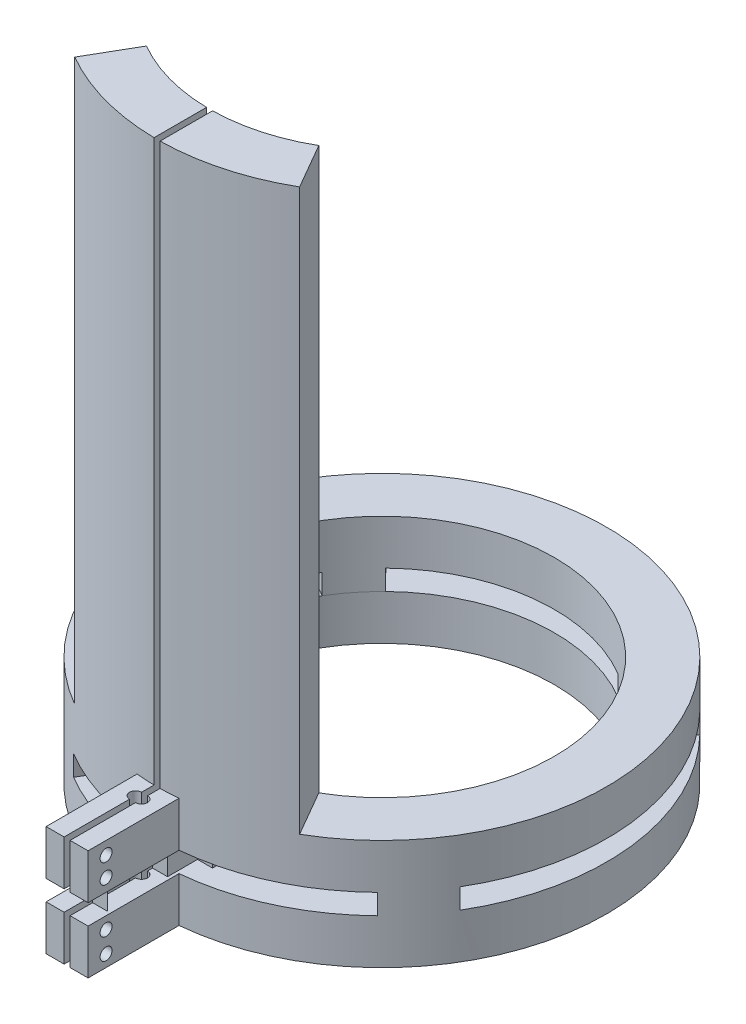
SolidWorks part; units mm, degrees
ref_plane "Front Plane" through (0, 0, 0) normal (0, 0, 1) x (1, 0, 0)
ref_plane "Top Plane" through (0, 0, 0) normal (0, 1, 0) x (1, 0, 0)
ref_plane "Right Plane" through (0, 0, 0) normal (1, 0, 0) x (0, 0, -1)
sketch "Sketch1" plane through (0, 0, 0) normal (0, 1, 0) x (1, 0, 0)
  circle A0 centre (0, 0) radius 57.5
  circle A1 centre (0, 0) radius 75
  dimension "D1" = 115
  dimension "D2" = 150
extrude "Boss-Extrude1" add sketch "Sketch1" along normal blind 15
ref_plane "Plane1" through (0, 0, 75) normal (0, 0, 1) x (1, 0, 0)
sketch "Sketch2" plane through (0, 0, 75) normal (0, 0, 1) x (1, 0, 0)
  line L0 (57.5, 15) -> (-57.5, 15) construction
  line L1 (-7, 15) -> (7, 15)
  line L2 (-7, 15) -> (-7, 0)
  line L3 (-7, 0) -> (7, 0)
  line L4 (7, 15) -> (7, 0)
  line L5 (-75, 0) -> (75, 0) construction
  line L6 (-75, 15) -> (-75, 0) construction
  dimension "D1" = 14
  dimension "D2" = 68
extrude "Boss-Extrude2" add sketch "Sketch2" along normal blind 30 and the other way blind 5
sketch "Sketch5" plane through (0, 0, 0) normal (0, -1, 0) x (1, 0, 0)
  line L0 (-1, 105) -> (-1, 57.4913)
  line L1 (-7, 105) -> (7, 105) construction
  line L2 (1, 105) -> (1, 57.4913)
  line L3 (-1, 105) -> (1, 105)
  line L4 (-1, 57.4913) -> (1, 57.4913)
  line L5 (-7, 74.6726) -> (-7, 105) construction
  line L6 (7, 74.6726) -> (7, 105) construction
  circle A0 centre (0, 0) radius 57.5 construction
  dimension "D1" = 6
  dimension "D2" = 6
extrude "Cut-Extrude2" cut sketch "Sketch5" against normal blind 64
sketch "Sketch6" plane through (7, 0, 0) normal (1, 0, 0) x (0, 0, -1)
  line L0 (-105, 0) -> (-105, 15) construction
  line L1 (-74.6726, 0) -> (-105, 0) construction
  line L2 (-74.6726, 15) -> (-105, 15) construction
  circle A0 centre (-99, 4.25) radius 2
  circle A1 centre (-99, 10.75) radius 2
  point P0 (-99, 4.25)
  point P1 (-99, 10.75)
  dimension "D5" = 4
  dimension "D6" = 4
  dimension "D1" = 6
  dimension "D2" = 6
  dimension "D3" = 4.25
  dimension "D4" = 4.25
extrude "Cut-Extrude3" cut sketch "Sketch6" against normal blind 64
sketch "Sketch7" plane through (0, 0, 0) normal (0, -1, 0) x (1, 0, 0)
  line L0 (1, 57.4913) -> (1, 105) construction
  line L2 (1, 67.4978) -> (1, 57.4978)
  line L3 (1, 57.4978) -> (11, 57.4978)
  line L4 (11, 67.4978) -> (11, 57.4978)
  line L5 (-6, 67.4913) -> (-6, 97.4913)
  line L6 (-1, 57.4913) -> (-10.5, 57.4913)
  line L8 (-6, 67.4913) -> (-10.5, 67.4913)
  line L9 (-10.5, 57.4913) -> (-10.5, 67.4913)
  line L10 (-6, 97.4913) -> (-1, 97.4913)
  line L11 (-1, 105) -> (-1, 57.4913) construction
  line L12 (-1, 97.4913) -> (-1, 57.4913)
  line L14 (1, 67.4978) -> (1, 97.4978)
  line L15 (1, 97.4978) -> (6, 97.4978)
  line L16 (6, 97.4978) -> (6, 67.4978)
  line L17 (6, 67.4978) -> (11, 67.4978)
  dimension "D1" = 10
  dimension "D2" = 10
  dimension "D3" = 30
  dimension "D4" = 10
  dimension "D5" = 5
  dimension "D6" = 5
  dimension "D7" = 30
extrude "Boss-Extrude3" add sketch "Sketch7" along normal blind 6.75
sketch "Sketch8" plane through (0, -6.75, 0) normal (0, -1, 0) x (1, 0, 0)
  line L0 (-1, 57.5043) -> (-1, 105)
  line L1 (-1, 105) -> (-7, 105)
  line L2 (-7, 105) -> (-7, 74.6726)
  line L3 (1, 57.5043) -> (1, 105)
  line L4 (1, 105) -> (7, 105)
  line L5 (7, 105) -> (7, 74.6726)
  arc A0 (-1, 57.5043) -> (1, 57.5043) centre (0, 0) ccw
  arc A1 (-7, 74.6726) -> (7, 74.6726) centre (0, 0) ccw
  dimension "D1" = 6
  dimension "D2" = 6
extrude "Boss-Extrude4" add sketch "Sketch8" along normal blind 15
sketch "Sketch10" plane through (-7, 0, 0) normal (-1, 0, 0) x (0, 0, 1)
  line L0 (105, -21.75) -> (74.6726, -21.75) construction
  line L1 (105, -21.75) -> (105, -6.75) construction
  line L2 (105, -6.75) -> (74.6726, -6.75) construction
  circle A0 centre (99, -10.75) radius 2
  circle A1 centre (99, -17.75) radius 2
  dimension "D3" = 4
  dimension "D4" = 4
  dimension "D1" = 4
  dimension "D2" = 6
  dimension "D5" = 6
  dimension "D6" = 4
extrude "Cut-Extrude5" cut sketch "Sketch10" against normal through all
sketch "Sketch11" plane through (-6, 0, 0) normal (-1, 0, 0) x (0, 0, 1)
  line L0 (97.4913, -6.75) -> (67.4913, -6.75) construction
  line L1 (97.4913, 0) -> (77.4913, 0)
  line L2 (97.4913, 0) -> (97.4913, -6.75)
  line L3 (97.4913, -6.75) -> (77.4913, -6.75)
  line L4 (77.4913, 0) -> (77.4913, -6.75)
  dimension "D1" = 20
extrude "Cut-Extrude6" cut sketch "Sketch11" against normal through all
sketch "Sketch12" plane through (0, -6.75, 0) normal (0, 1, 0) x (1, 0, 0)
  line L0 (52.2865, -53.7691) -> (40.0863, -41.223)
  line L2 (49.3897, -29.4432) -> (64.4214, -38.4042)
  line L3 (-53.7691, -52.2865) -> (-41.223, -40.0863)
  line L4 (-29.4432, -49.3897) -> (-38.4042, -64.4214)
  line L5 (-52.2865, 53.7691) -> (-40.0863, 41.223)
  line L6 (-49.3897, 29.4432) -> (-64.4214, 38.4042)
  line L7 (53.7691, 52.2865) -> (41.223, 40.0863)
  line L8 (29.4432, 49.3897) -> (38.4042, 64.4214)
  arc A0 (40.0863, -41.223) -> (49.3897, -29.4432) centre (0, 0) ccw
  arc A1 (52.2865, -53.7691) -> (64.4214, -38.4042) centre (0, 0) ccw
  arc A3 (-53.7691, -52.2865) -> (-38.4042, -64.4214) centre (0, 0) ccw
  arc A4 (-41.223, -40.0863) -> (-29.4432, -49.3897) centre (0, 0) ccw
  arc A5 (-52.2865, 53.7691) -> (-64.4214, 38.4042) centre (0, 0) ccw
  arc A6 (-40.0863, 41.223) -> (-49.3897, 29.4432) centre (0, 0) ccw
  arc A7 (53.7691, 52.2865) -> (38.4042, 64.4214) centre (0, 0) ccw
  arc A8 (41.223, 40.0863) -> (29.4432, 49.3897) centre (0, 0) ccw
  point P21 (0, 0)
  dimension "D1" = 57.5
  dimension "D2" = 15
  dimension "D3" = 4
extrude "Boss-Extrude5" add sketch "Sketch12" along normal up to surface (6.75 mm away) up to face at (0.6957, 0, 67.9162)
sketch "Sketch15" plane through (0, 15, 0) normal (0, 1, 0) x (1, 0, 0)
  line L1 (-1, -83.1726) -> (-1, -79.1726)
  line L4 (1, -83.1726) -> (1, -79.1726)
  arc A0 (-1, -79.1726) -> (-1, -83.1726) centre (-1, -81.1726) ccw
  arc A3 (1, -83.1726) -> (1, -79.1726) centre (1, -81.1726) ccw
  dimension "D1" = 4
  dimension "D2" = 6.5
  dimension "D3" = 4
extrude "Cut-Extrude8" cut sketch "Sketch15" against normal through all
sketch "Sketch16" plane through (0, 15, 0) normal (0, 1, 0) x (1, 0, 0)
  line L0 (-1, -74.9933) -> (-1, -57.4913)
  line L2 (1, -74.9933) -> (1, -57.4913)
  line L4 (-37.5, -64.9519) -> (-28.75, -49.7965)
  line L6 (37.5, -64.9519) -> (28.75, -49.7965)
  arc A0 (1, -74.9933) -> (37.5, -64.9519) centre (0, 0) ccw
  arc A1 (1, -57.4913) -> (28.75, -49.7965) centre (0, 0) ccw
  arc A5 (-37.5, -64.9519) -> (-1, -74.9933) centre (0, 0) ccw
  arc A6 (-28.75, -49.7965) -> (-1, -57.4913) centre (0, 0) ccw
  dimension "D1" = 115
  dimension "D2" = 150
  dimension "D3" = 30
extrude "Boss-Extrude6" add sketch "Sketch16" along normal blind 187
